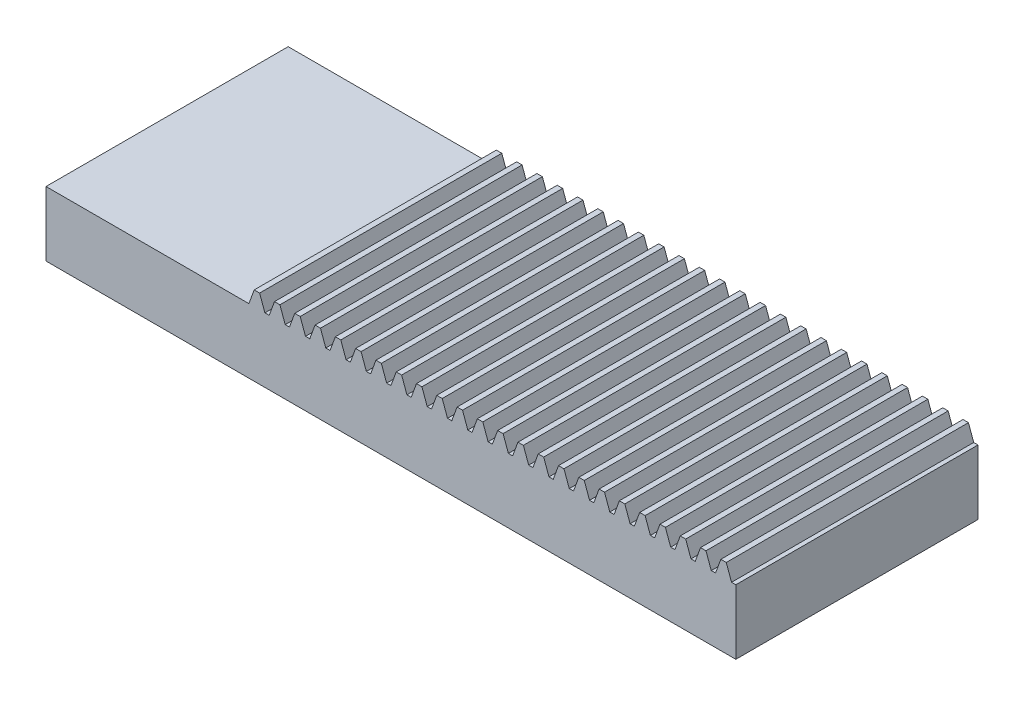
SolidWorks part; units mm, degrees
material "1.1193 (C45G)"
ref_plane "Front" through (0, 0, 0) normal (0, 0, 1) x (1, 0, 0)
ref_plane "Top" through (0, 0, 0) normal (0, 1, 0) x (1, 0, 0)
ref_plane "Right" through (0, 0, 0) normal (1, 0, 0) x (0, 0, -1)
sketch "Sketch1" plane through (0, 0, 0) normal (0, 0, 1) x (1, 0, 0)
  line L1 (0, 0) -> (85.4513, 0)
  line L2 (0, 0) -> (0, -8)
  line L3 (0, -8) -> (85.4513, -8)
  line L4 (85.4513, 0) -> (85.4513, -8)
  dimension "D1" = 8
  dimension "L" = 85.4513
extrude "Extrude1" add sketch "Sketch1" along normal blind 30
sketch "Sketch2" plane through (0, 0, 30) normal (0, 0, 1) x (1, 0, 0)
  line L0 (0, 0) -> (0.6551, 1.8)
  line L1 (0.6551, 1.8) -> (1.3294, 1.8)
  line L2 (1.3294, 1.8) -> (1.9846, 0)
  line L3 (85.4513, 0) -> (0, 0) construction
  line L4 (0, 0) -> (1.9846, 0)
  line L5 (0.364, 1) -> (1.6206, 1) construction
  dimension "alpha2" = 70
  dimension "alpha" = 110
  dimension "ha" = 0.8
  dimension "hf" = 1
  dimension "S" = 1.2566
extrude "Extrude2" add sketch "Sketch2" against normal up to surface (30 mm away) up to face at (42.7257, -4, 0)
pattern_linear "LPattern1" count 34 spacing 2.5133 along (1, 0, 0) of "Extrude2"
sketch "草图1" plane through (0, 0, 30) normal (0, 0, 1) x (1, 0, 0)
  line L0 (85.4513, -8) -> (85.4513, 0) construction
  line L1 (0, 0) -> (24.9513, 0)
  line L2 (0, 0) -> (0, 8.7022)
  line L3 (0, 8.7022) -> (24.9513, 8.7022)
  line L4 (24.9513, 0) -> (24.9513, 8.7022)
  dimension "D1" = 60.5
extrude "切除-拉伸1" cut sketch "草图1" against normal blind 40
